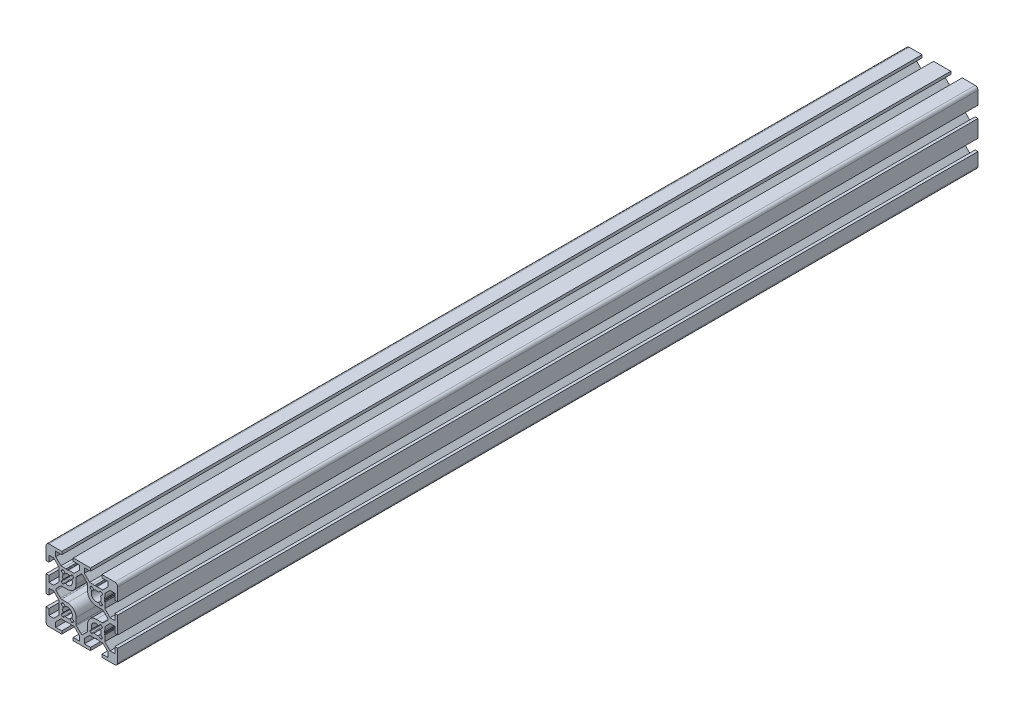
SolidWorks part; units mm, degrees
ref_plane "Front Plane" through (0, 0, 0) normal (0, 0, 1) x (1, 0, 0)
ref_plane "Top Plane" through (0, 0, 0) normal (0, 1, 0) x (1, 0, 0)
ref_plane "Right Plane" through (0, 0, 0) normal (1, 0, 0) x (0, 0, -1)
ref_plane "Plane1" through (0, 0, 0) normal (0, 0, 1) x (1, 0, 0)
sketch "Sketch1" plane through (0, 0, 0) normal (0, 0, 1) x (1, 0, 0)
  line L0 (-25, 23) -> (-25, 14)
  line L1 (-25, 14) -> (-23, 14)
  line L2 (-23, 14) -> (-23, 18.25)
  line L3 (-23, 18.25) -> (-19.6642, 18.25)
  line L4 (-19.6642, 18.25) -> (-16, 14.5858)
  line L5 (-16, 14.5858) -> (-16, 10.6536)
  line L6 (-15.933, 10.4036) -> (-15.7, 10)
  line L7 (-15.7, 10) -> (-15.933, 9.5964)
  line L8 (-15.933, 9.0964) -> (-15.751, 8.7811)
  line L9 (-15.751, 8.7811) -> (-16, 7.5)
  line L10 (-16, 7.5) -> (-16, 5.4142)
  line L11 (-16, 5.4142) -> (-19.6642, 1.75)
  line L12 (-19.6642, 1.75) -> (-23, 1.75)
  line L13 (-23, 1.75) -> (-23, 6)
  line L14 (-23, 6) -> (-25, 6)
  line L15 (-25, 6) -> (-25, -6)
  line L16 (-25, -6) -> (-23, -6)
  line L17 (-23, -6) -> (-23, -1.75)
  line L18 (-23, -1.75) -> (-19.6642, -1.75)
  line L19 (-19.6642, -1.75) -> (-16, -5.4142)
  line L20 (-16, -5.4142) -> (-16, -9.3464)
  line L21 (-15.933, -9.5964) -> (-15.7, -10)
  line L22 (-15.7, -10) -> (-15.933, -10.4036)
  line L23 (-15.933, -10.9036) -> (-15.751, -11.2189)
  line L24 (-15.751, -11.2189) -> (-16, -12.5)
  line L25 (-16, -12.5) -> (-16, -14.5858)
  line L26 (-16, -14.5858) -> (-19.6642, -18.25)
  line L27 (-19.6642, -18.25) -> (-23, -18.25)
  line L28 (-23, -18.25) -> (-23, -14)
  line L29 (-23, -14) -> (-25, -14)
  line L30 (-25, -14) -> (-25, -23)
  line L31 (-23, -25) -> (-14, -25)
  line L32 (-14, -25) -> (-14, -23)
  line L33 (-14, -23) -> (-18.25, -23)
  line L34 (-18.25, -23) -> (-18.25, -19.6642)
  line L35 (-18.25, -19.6642) -> (-14.5858, -16)
  line L36 (-14.5858, -16) -> (-10.6536, -16)
  line L37 (-10.4036, -15.933) -> (-10, -15.7)
  line L38 (-10, -15.7) -> (-9.5964, -15.933)
  line L39 (-9.0964, -15.933) -> (-8.7811, -15.751)
  line L40 (-8.7811, -15.751) -> (-7.5, -16)
  line L41 (-7.5, -16) -> (-5.4142, -16)
  line L42 (-5.4142, -16) -> (-1.75, -19.6642)
  line L43 (-1.75, -19.6642) -> (-1.75, -23)
  line L44 (-1.75, -23) -> (-6, -23)
  line L45 (-6, -23) -> (-6, -25)
  line L46 (-6, -25) -> (6, -25)
  line L47 (6, -25) -> (6, -23)
  line L48 (6, -23) -> (1.75, -23)
  line L49 (1.75, -23) -> (1.75, -19.6642)
  line L50 (1.75, -19.6642) -> (5.4142, -16)
  line L51 (5.4142, -16) -> (9.3464, -16)
  line L52 (9.5964, -15.933) -> (10, -15.7)
  line L53 (10, -15.7) -> (10.4036, -15.933)
  line L54 (10.9036, -15.933) -> (11.2189, -15.751)
  line L55 (11.2189, -15.751) -> (12.5, -16)
  line L56 (12.5, -16) -> (14.5858, -16)
  line L57 (14.5858, -16) -> (18.25, -19.6642)
  line L58 (18.25, -19.6642) -> (18.25, -23)
  line L59 (18.25, -23) -> (14, -23)
  line L60 (14, -23) -> (14, -25)
  line L61 (14, -25) -> (23, -25)
  line L62 (25, -23) -> (25, -14)
  line L63 (25, -14) -> (23, -14)
  line L64 (23, -14) -> (23, -18.25)
  line L65 (23, -18.25) -> (19.6642, -18.25)
  line L66 (19.6642, -18.25) -> (16, -14.5858)
  line L67 (16, -14.5858) -> (16, -10.6536)
  line L68 (15.933, -10.4036) -> (15.7, -10)
  line L69 (15.7, -10) -> (15.933, -9.5964)
  line L70 (15.933, -9.0964) -> (15.751, -8.7811)
  line L71 (15.751, -8.7811) -> (16, -7.5)
  line L72 (16, -7.5) -> (16, -5.4142)
  line L73 (16, -5.4142) -> (19.6642, -1.75)
  line L74 (19.6642, -1.75) -> (23, -1.75)
  line L75 (23, -1.75) -> (23, -6)
  line L76 (23, -6) -> (25, -6)
  line L77 (25, -6) -> (25, 6)
  line L78 (25, 6) -> (23, 6)
  line L79 (23, 6) -> (23, 1.75)
  line L80 (23, 1.75) -> (19.6642, 1.75)
  line L81 (19.6642, 1.75) -> (16, 5.4142)
  line L82 (16, 5.4142) -> (16, 9.3464)
  line L83 (15.933, 9.5964) -> (15.7, 10)
  line L84 (15.7, 10) -> (15.933, 10.4036)
  line L85 (15.933, 10.9036) -> (15.751, 11.2189)
  line L86 (15.751, 11.2189) -> (16, 12.5)
  line L87 (16, 12.5) -> (16, 14.5858)
  line L88 (16, 14.5858) -> (19.6642, 18.25)
  line L89 (19.6642, 18.25) -> (23, 18.25)
  line L90 (23, 18.25) -> (23, 14)
  line L91 (23, 14) -> (25, 14)
  line L92 (25, 14) -> (25, 23)
  line L93 (23, 25) -> (14, 25)
  line L94 (14, 25) -> (14, 23)
  line L95 (14, 23) -> (18.25, 23)
  line L96 (18.25, 23) -> (18.25, 19.6642)
  line L97 (18.25, 19.6642) -> (14.5858, 16)
  line L98 (14.5858, 16) -> (10.6536, 16)
  line L99 (10.4036, 15.933) -> (10, 15.7)
  line L100 (10, 15.7) -> (9.5964, 15.933)
  line L101 (9.0964, 15.933) -> (8.7811, 15.751)
  line L102 (8.7811, 15.751) -> (7.5, 16)
  line L103 (7.5, 16) -> (5.4142, 16)
  line L104 (5.4142, 16) -> (1.75, 19.6642)
  line L105 (1.75, 19.6642) -> (1.75, 23)
  line L106 (1.75, 23) -> (6, 23)
  line L107 (6, 23) -> (6, 25)
  line L108 (6, 25) -> (-6, 25)
  line L109 (-6, 25) -> (-6, 23)
  line L110 (-6, 23) -> (-1.75, 23)
  line L111 (-1.75, 23) -> (-1.75, 19.6642)
  line L112 (-1.75, 19.6642) -> (-5.4142, 16)
  line L113 (-5.4142, 16) -> (-9.3464, 16)
  line L114 (-9.5964, 15.933) -> (-10, 15.7)
  line L115 (-10, 15.7) -> (-10.4036, 15.933)
  line L116 (-10.9036, 15.933) -> (-11.2189, 15.751)
  line L117 (-11.2189, 15.751) -> (-12.5, 16)
  line L118 (-12.5, 16) -> (-14.5858, 16)
  line L119 (-14.5858, 16) -> (-18.25, 19.6642)
  line L120 (-18.25, 19.6642) -> (-18.25, 23)
  line L121 (-18.25, 23) -> (-14, 23)
  line L122 (-14, 23) -> (-14, 25)
  line L123 (-14, 25) -> (-23, 25)
  line L124 (-17.8787, -0.7071) -> (-14.8787, -3.7071)
  line L125 (-14.1716, -4) -> (-10, -4)
  line L126 (-4, -10) -> (-4, -14.1716)
  line L127 (-3.7071, -14.8787) -> (-0.7071, -17.8787)
  line L128 (0.7071, -17.8787) -> (3.7071, -14.8787)
  line L129 (4, -14.1716) -> (4, -10)
  line L130 (10, -4) -> (14.1716, -4)
  line L131 (14.8787, -3.7071) -> (17.8787, -0.7071)
  line L132 (17.8787, 0.7071) -> (14.8787, 3.7071)
  line L133 (14.1716, 4) -> (10, 4)
  line L134 (4, 10) -> (4, 14.1716)
  line L135 (3.7071, 14.8787) -> (0.7071, 17.8787)
  line L136 (-0.7071, 17.8787) -> (-3.7071, 14.8787)
  line L137 (-4, 14.1716) -> (-4, 10)
  line L138 (-10, 4) -> (-14.1716, 4)
  line L139 (-14.8787, 3.7071) -> (-17.8787, 0.7071)
  arc A0 (-16, 10.6536) -> (-15.933, 10.4036) centre (-15.5, 10.6536) ccw
  arc A1 (-15.933, 9.5964) -> (-15.933, 9.0964) centre (-15.5, 9.3464) ccw
  arc A2 (-16, -9.3464) -> (-15.933, -9.5964) centre (-15.5, -9.3464) ccw
  arc A3 (-15.933, -10.4036) -> (-15.933, -10.9036) centre (-15.5, -10.6536) ccw
  arc A4 (-25, -23) -> (-23, -25) centre (-23, -23) ccw
  arc A5 (-10.6536, -16) -> (-10.4036, -15.933) centre (-10.6536, -15.5) ccw
  arc A6 (-9.5964, -15.933) -> (-9.0964, -15.933) centre (-9.3464, -15.5) ccw
  arc A7 (9.3464, -16) -> (9.5964, -15.933) centre (9.3464, -15.5) ccw
  arc A8 (10.4036, -15.933) -> (10.9036, -15.933) centre (10.6536, -15.5) ccw
  arc A9 (23, -25) -> (25, -23) centre (23, -23) ccw
  arc A10 (16, -10.6536) -> (15.933, -10.4036) centre (15.5, -10.6536) ccw
  arc A11 (15.933, -9.5964) -> (15.933, -9.0964) centre (15.5, -9.3464) ccw
  arc A12 (16, 9.3464) -> (15.933, 9.5964) centre (15.5, 9.3464) ccw
  arc A13 (15.933, 10.4036) -> (15.933, 10.9036) centre (15.5, 10.6536) ccw
  arc A14 (25, 23) -> (23, 25) centre (23, 23) ccw
  arc A15 (10.6536, 16) -> (10.4036, 15.933) centre (10.6536, 15.5) ccw
  arc A16 (9.5964, 15.933) -> (9.0964, 15.933) centre (9.3464, 15.5) ccw
  arc A17 (-9.3464, 16) -> (-9.5964, 15.933) centre (-9.3464, 15.5) ccw
  arc A18 (-10.4036, 15.933) -> (-10.9036, 15.933) centre (-10.6536, 15.5) ccw
  arc A19 (-23, 25) -> (-25, 23) centre (-23, 23) ccw
  arc A20 (-17.8787, 0.7071) -> (-17.8787, -0.7071) centre (-17.1716, 0) ccw
  arc A21 (-14.8787, -3.7071) -> (-14.1716, -4) centre (-14.1716, -3) ccw
  arc A22 (-10, -4) -> (-4, -10) centre (-10, -10) cw
  arc A23 (-4, -14.1716) -> (-3.7071, -14.8787) centre (-3, -14.1716) ccw
  arc A24 (-0.7071, -17.8787) -> (0.7071, -17.8787) centre (0, -17.1716) ccw
  arc A25 (3.7071, -14.8787) -> (4, -14.1716) centre (3, -14.1716) ccw
  arc A26 (4, -10) -> (10, -4) centre (10, -10) cw
  arc A27 (14.1716, -4) -> (14.8787, -3.7071) centre (14.1716, -3) ccw
  arc A28 (17.8787, -0.7071) -> (17.8787, 0.7071) centre (17.1716, 0) ccw
  arc A29 (14.8787, 3.7071) -> (14.1716, 4) centre (14.1716, 3) ccw
  arc A30 (10, 4) -> (4, 10) centre (10, 10) cw
  arc A31 (4, 14.1716) -> (3.7071, 14.8787) centre (3, 14.1716) ccw
  arc A32 (0.7071, 17.8787) -> (-0.7071, 17.8787) centre (0, 17.1716) ccw
  arc A33 (-3.7071, 14.8787) -> (-4, 14.1716) centre (-3, 14.1716) ccw
  arc A34 (-4, 10) -> (-10, 4) centre (-10, 10) cw
  arc A35 (-14.1716, 4) -> (-14.8787, 3.7071) centre (-14.1716, 3) ccw
extrude "Boss-Extrude1" add sketch "Sketch1" against normal blind 600
ref_plane "Plane2" through (0, 0, 0) normal (0, 0, 1) x (1, 0, 0)
sketch "Sketch2" plane through (0, 0, 0) normal (0, 0, 1) x (1, 0, 0)
  line L0 (-14.2426, 12.8284) -> (-13.2051, 11.7909)
  line L1 (-13.2051, 8.2091) -> (-14.2426, 7.1716)
  line L2 (-14.2426, 6.4645) -> (-13.5355, 5.7574)
  line L3 (-12.8284, 5.7574) -> (-11.7909, 6.7949)
  line L4 (-6.7949, 11.7909) -> (-5.7574, 12.8284)
  line L5 (-5.7574, 13.5355) -> (-6.4645, 14.2426)
  line L6 (-7.1716, 14.2426) -> (-8.2091, 13.2051)
  line L7 (-11.7909, 13.2051) -> (-12.8284, 14.2426)
  line L8 (-13.5355, 14.2426) -> (-14.2426, 13.5355)
  arc A0 (-14.2426, 13.5355) -> (-14.2426, 12.8284) centre (-13.8891, 13.182) ccw
  arc A1 (-13.2051, 11.7909) -> (-13.1208, 11.3493) centre (-13.4879, 11.508) cw
  arc A2 (-13.1208, 11.3493) -> (-13.1208, 8.6507) centre (-10, 10) ccw
  arc A3 (-13.1208, 8.6507) -> (-13.2051, 8.2091) centre (-13.4879, 8.492) cw
  arc A4 (-14.2426, 7.1716) -> (-14.2426, 6.4645) centre (-13.8891, 6.818) ccw
  arc A5 (-13.5355, 5.7574) -> (-12.8284, 5.7574) centre (-13.182, 6.1109) ccw
  arc A6 (-11.7909, 6.7949) -> (-11.3493, 6.8792) centre (-11.508, 6.5121) cw
  arc A7 (-11.3493, 6.8792) -> (-6.8792, 11.3493) centre (-10, 10) ccw
  arc A8 (-6.8792, 11.3493) -> (-6.7949, 11.7909) centre (-6.5121, 11.508) cw
  arc A9 (-5.7574, 12.8284) -> (-5.7574, 13.5355) centre (-6.1109, 13.182) ccw
  arc A10 (-6.4645, 14.2426) -> (-7.1716, 14.2426) centre (-6.818, 13.8891) ccw
  arc A11 (-8.2091, 13.2051) -> (-8.6507, 13.1208) centre (-8.492, 13.4879) cw
  arc A12 (-8.6507, 13.1208) -> (-11.3493, 13.1208) centre (-10, 10) ccw
  arc A13 (-11.3493, 13.1208) -> (-11.7909, 13.2051) centre (-11.508, 13.4879) cw
  arc A14 (-12.8284, 14.2426) -> (-13.5355, 14.2426) centre (-13.182, 13.8891) ccw
extrude "Cut-Extrude1" cut sketch "Sketch2" against normal through all
ref_plane "Plane3" through (0, 0, 0) normal (0, 0, 1) x (1, 0, 0)
sketch "Sketch3" plane through (0, 0, 0) normal (0, 0, 1) x (1, 0, 0)
  line L0 (-12.8284, -14.2426) -> (-11.7909, -13.2051)
  line L1 (-8.2091, -13.2051) -> (-7.1716, -14.2426)
  line L2 (-6.4645, -14.2426) -> (-5.7574, -13.5355)
  line L3 (-5.7574, -12.8284) -> (-6.7949, -11.7909)
  line L4 (-11.7909, -6.7949) -> (-12.8284, -5.7574)
  line L5 (-13.5355, -5.7574) -> (-14.2426, -6.4645)
  line L6 (-14.2426, -7.1716) -> (-13.2051, -8.2091)
  line L7 (-13.2051, -11.7909) -> (-14.2426, -12.8284)
  line L8 (-14.2426, -13.5355) -> (-13.5355, -14.2426)
  arc A0 (-13.5355, -14.2426) -> (-12.8284, -14.2426) centre (-13.182, -13.8891) ccw
  arc A1 (-11.7909, -13.2051) -> (-11.3493, -13.1208) centre (-11.508, -13.4879) cw
  arc A2 (-11.3493, -13.1208) -> (-8.6507, -13.1208) centre (-10, -10) ccw
  arc A3 (-8.6507, -13.1208) -> (-8.2091, -13.2051) centre (-8.492, -13.4879) cw
  arc A4 (-7.1716, -14.2426) -> (-6.4645, -14.2426) centre (-6.818, -13.8891) ccw
  arc A5 (-5.7574, -13.5355) -> (-5.7574, -12.8284) centre (-6.1109, -13.182) ccw
  arc A6 (-6.7949, -11.7909) -> (-6.8792, -11.3493) centre (-6.5121, -11.508) cw
  arc A7 (-6.8792, -11.3493) -> (-11.3493, -6.8792) centre (-10, -10) ccw
  arc A8 (-11.3493, -6.8792) -> (-11.7909, -6.7949) centre (-11.508, -6.5121) cw
  arc A9 (-12.8284, -5.7574) -> (-13.5355, -5.7574) centre (-13.182, -6.1109) ccw
  arc A10 (-14.2426, -6.4645) -> (-14.2426, -7.1716) centre (-13.8891, -6.818) ccw
  arc A11 (-13.2051, -8.2091) -> (-13.1208, -8.6507) centre (-13.4879, -8.492) cw
  arc A12 (-13.1208, -8.6507) -> (-13.1208, -11.3493) centre (-10, -10) ccw
  arc A13 (-13.1208, -11.3493) -> (-13.2051, -11.7909) centre (-13.4879, -11.508) cw
  arc A14 (-14.2426, -12.8284) -> (-14.2426, -13.5355) centre (-13.8891, -13.182) ccw
extrude "Cut-Extrude2" cut sketch "Sketch3" against normal through all
ref_plane "Plane4" through (0, 0, 0) normal (0, 0, 1) x (1, 0, 0)
sketch "Sketch4" plane through (0, 0, 0) normal (0, 0, 1) x (1, 0, 0)
  line L0 (14.2426, -12.8284) -> (13.2051, -11.7909)
  line L1 (13.2051, -8.2091) -> (14.2426, -7.1716)
  line L2 (14.2426, -6.4645) -> (13.5355, -5.7574)
  line L3 (12.8284, -5.7574) -> (11.7909, -6.7949)
  line L4 (6.7949, -11.7909) -> (5.7574, -12.8284)
  line L5 (5.7574, -13.5355) -> (6.4645, -14.2426)
  line L6 (7.1716, -14.2426) -> (8.2091, -13.2051)
  line L7 (11.7909, -13.2051) -> (12.8284, -14.2426)
  line L8 (13.5355, -14.2426) -> (14.2426, -13.5355)
  arc A0 (14.2426, -13.5355) -> (14.2426, -12.8284) centre (13.8891, -13.182) ccw
  arc A1 (13.2051, -11.7909) -> (13.1208, -11.3493) centre (13.4879, -11.508) cw
  arc A2 (13.1208, -11.3493) -> (13.1208, -8.6507) centre (10, -10) ccw
  arc A3 (13.1208, -8.6507) -> (13.2051, -8.2091) centre (13.4879, -8.492) cw
  arc A4 (14.2426, -7.1716) -> (14.2426, -6.4645) centre (13.8891, -6.818) ccw
  arc A5 (13.5355, -5.7574) -> (12.8284, -5.7574) centre (13.182, -6.1109) ccw
  arc A6 (11.7909, -6.7949) -> (11.3493, -6.8792) centre (11.508, -6.5121) cw
  arc A7 (11.3493, -6.8792) -> (6.8792, -11.3493) centre (10, -10) ccw
  arc A8 (6.8792, -11.3493) -> (6.7949, -11.7909) centre (6.5121, -11.508) cw
  arc A9 (5.7574, -12.8284) -> (5.7574, -13.5355) centre (6.1109, -13.182) ccw
  arc A10 (6.4645, -14.2426) -> (7.1716, -14.2426) centre (6.818, -13.8891) ccw
  arc A11 (8.2091, -13.2051) -> (8.6507, -13.1208) centre (8.492, -13.4879) cw
  arc A12 (8.6507, -13.1208) -> (11.3493, -13.1208) centre (10, -10) ccw
  arc A13 (11.3493, -13.1208) -> (11.7909, -13.2051) centre (11.508, -13.4879) cw
  arc A14 (12.8284, -14.2426) -> (13.5355, -14.2426) centre (13.182, -13.8891) ccw
extrude "Cut-Extrude3" cut sketch "Sketch4" against normal through all
ref_plane "Plane5" through (0, 0, 0) normal (0, 0, 1) x (1, 0, 0)
sketch "Sketch5" plane through (0, 0, 0) normal (0, 0, 1) x (1, 0, 0)
  line L0 (12.8284, 14.2426) -> (11.7909, 13.2051)
  line L1 (8.2091, 13.2051) -> (7.1716, 14.2426)
  line L2 (6.4645, 14.2426) -> (5.7574, 13.5355)
  line L3 (5.7574, 12.8284) -> (6.7949, 11.7909)
  line L4 (11.7909, 6.7949) -> (12.8284, 5.7574)
  line L5 (13.5355, 5.7574) -> (14.2426, 6.4645)
  line L6 (14.2426, 7.1716) -> (13.2051, 8.2091)
  line L7 (13.2051, 11.7909) -> (14.2426, 12.8284)
  line L8 (14.2426, 13.5355) -> (13.5355, 14.2426)
  arc A0 (13.5355, 14.2426) -> (12.8284, 14.2426) centre (13.182, 13.8891) ccw
  arc A1 (11.7909, 13.2051) -> (11.3493, 13.1208) centre (11.508, 13.4879) cw
  arc A2 (11.3493, 13.1208) -> (8.6507, 13.1208) centre (10, 10) ccw
  arc A3 (8.6507, 13.1208) -> (8.2091, 13.2051) centre (8.492, 13.4879) cw
  arc A4 (7.1716, 14.2426) -> (6.4645, 14.2426) centre (6.818, 13.8891) ccw
  arc A5 (5.7574, 13.5355) -> (5.7574, 12.8284) centre (6.1109, 13.182) ccw
  arc A6 (6.7949, 11.7909) -> (6.8792, 11.3493) centre (6.5121, 11.508) cw
  arc A7 (6.8792, 11.3493) -> (11.3493, 6.8792) centre (10, 10) ccw
  arc A8 (11.3493, 6.8792) -> (11.7909, 6.7949) centre (11.508, 6.5121) cw
  arc A9 (12.8284, 5.7574) -> (13.5355, 5.7574) centre (13.182, 6.1109) ccw
  arc A10 (14.2426, 6.4645) -> (14.2426, 7.1716) centre (13.8891, 6.818) ccw
  arc A11 (13.2051, 8.2091) -> (13.1208, 8.6507) centre (13.4879, 8.492) cw
  arc A12 (13.1208, 8.6507) -> (13.1208, 11.3493) centre (10, 10) ccw
  arc A13 (13.1208, 11.3493) -> (13.2051, 11.7909) centre (13.4879, 11.508) cw
  arc A14 (14.2426, 12.8284) -> (14.2426, 13.5355) centre (13.8891, 13.182) ccw
extrude "Cut-Extrude4" cut sketch "Sketch5" against normal through all
